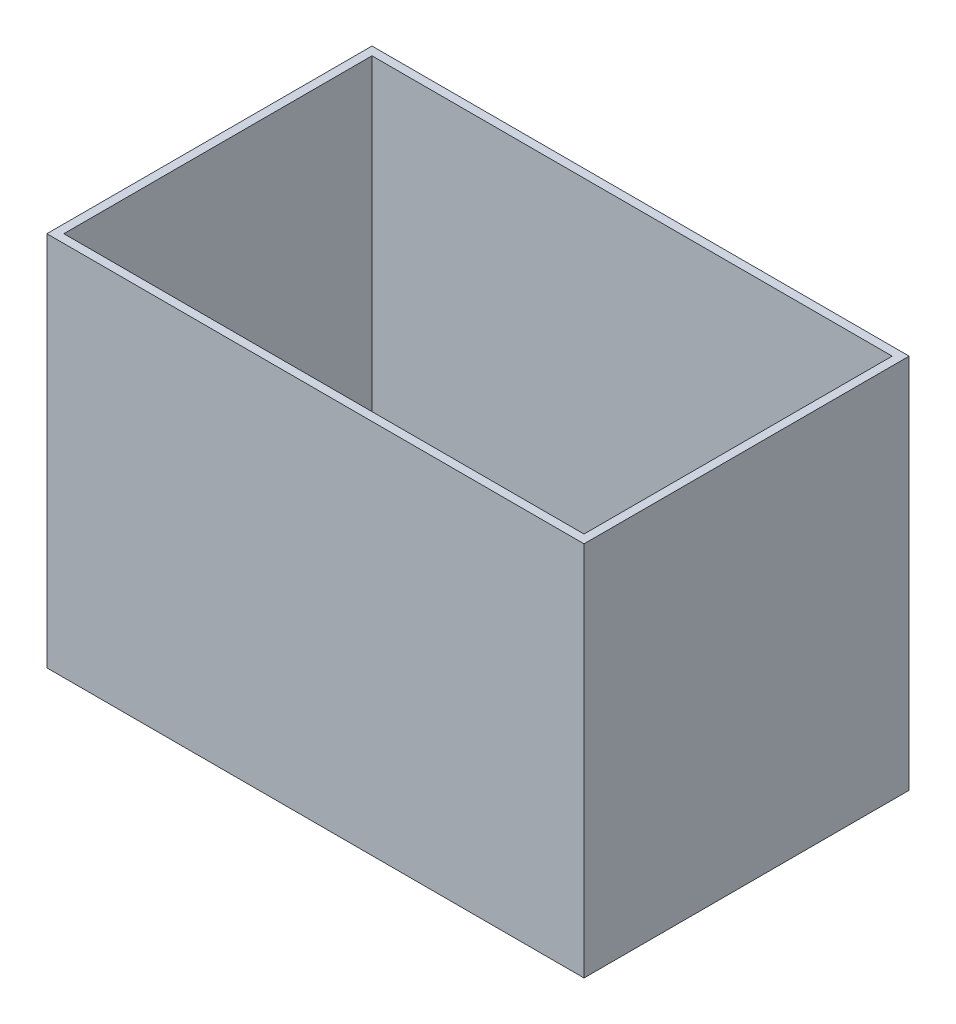
SolidWorks part; units mm, degrees
material "Glass"
ref_plane "Front" through (0, 0, 0) normal (0, 0, 1) x (1, 0, 0)
ref_plane "Top" through (0, 0, 0) normal (0, 1, 0) x (1, 0, 0)
ref_plane "Right" through (0, 0, 0) normal (1, 0, 0) x (0, 0, -1)
sketch "Sketch1" plane through (0, 0, 0) normal (0, 1, 0) x (1, 0, 0)
  line L1 (0, 0) -> (380, 0)
  line L2 (0, 0) -> (0, -230)
  line L3 (0, -230) -> (380, -230)
  line L4 (380, 0) -> (380, -230)
  dimension "D1" = 380
  dimension "D2" = 230
extrude "Boss-Extrude1" add sketch "Sketch1" along normal blind 6
sketch "Sketch2" plane through (0, 6, 0) normal (0, 1, 0) x (1, 0, 0)
  line L0 (6, -224) -> (6, -6)
  line L1 (0, -230) -> (380, -230)
  line L2 (0, -230) -> (0, 0)
  line L3 (0, 0) -> (380, 0)
  line L4 (380, -230) -> (380, 0)
  line L5 (6, -6) -> (374, -6)
  line L6 (374, -224) -> (374, -6)
  line L7 (6, -224) -> (374, -224)
  dimension "D1" = 6
extrude "Boss-Extrude2" add sketch "Sketch2" along normal blind 260
